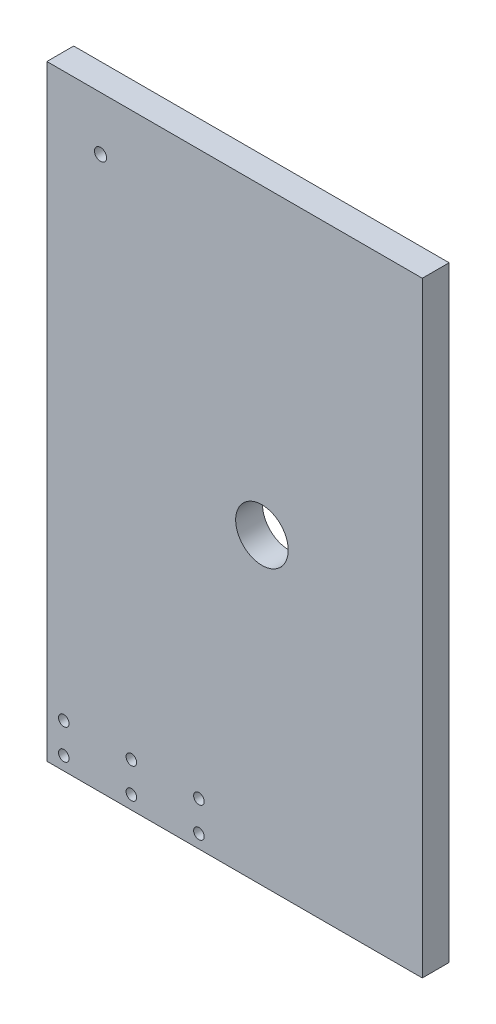
SolidWorks part; units mm, degrees
material "Balsa"
ref_plane "Front Plane" through (0, 0, 0) normal (0, 0, 1) x (1, 0, 0)
ref_plane "Top Plane" through (0, 0, 0) normal (0, 1, 0) x (1, 0, 0)
ref_plane "Right Plane" through (0, 0, 0) normal (1, 0, 0) x (0, 0, -1)
sketch "Sketch1" plane through (0, 0, 0) normal (0, 0, 1) x (1, 0, 0)
  line L0 (-63.5, 59.055) -> (-25.2727, 0.1003) construction
  line L1 (-76.2, 71.755) -> (76.2, 71.755)
  line L2 (-76.2, 71.755) -> (-76.2, -71.755)
  line L3 (-76.2, -71.755) -> (76.2, -71.755)
  line L4 (76.2, 71.755) -> (76.2, -71.755)
  line L5 (-76.2, 71.755) -> (76.2, -71.755) construction
  line L6 (-76.2, -71.755) -> (76.2, 71.755) construction
  line L7 (-25.2727, 0.1003) -> (-63.5159, 0.1003) construction
  circle A0 centre (-63.5, 59.055) radius 1.4375
  circle A1 centre (-25.2727, 0.1003) radius 6.223
  point P0 (0, 0)
  dimension "D1" = 12.446
  dimension "D2" = 70.2637
  dimension "D4" = 2.875
  dimension "D3" = 57.04
  dimension "D5" = 152.4
  dimension "D6" = 71.6547
  dimension "D7" = 12.7
  dimension "D8" = 12.7
  dimension "D9" = 143.51
extrude "Boss-Extrude1" add sketch "Sketch1" along normal blind 6.35 contours L4 L1 L2 L3 A1 A0
sketch "Sketch2" plane through (0, 0, 6.35) normal (0, 0, 1) x (1, 0, 0)
  line L1 (76.2, 71.755) -> (76.2, -71.755) construction
  line L2 (-66.0896, -64.5997) -> (90.0227, -64.5997) construction
  circle A0 centre (63.5, 11.6003) radius 76.2 construction
  circle A1 centre (63.5, 11.6003) radius 3.1115
  circle A2 centre (-25.2727, 0.1003) radius 6.223 construction
  dimension "D1" = 152.4
  dimension "D4" = 64.7
  dimension "D2" = 6.223
  dimension "D3" = 12.7
extrude "Cut-Extrude1" cut sketch "Sketch2" against normal through all contours A1
sketch "Sketch3" plane through (0, 0, 6.35) normal (0, 0, 1) x (1, 0, 0)
  circle A0 centre (-25.2727, 0.1003) radius 18.75 construction
  circle A1 centre (9.6146, -13.6519) radius 18.75 construction
  dimension "D1" = 37.5
sketch "Sketch4" plane through (0, 0, 6.35) normal (0, 0, 1) x (1, 0, 0)
  circle A0 centre (43.8491, -5.2749) radius 1.625
  circle A1 centre (43.8491, -21.2749) radius 1.625
  circle A2 centre (43.8491, -37.2749) radius 1.625
  circle A3 centre (43.8491, 10.7251) radius 1.625
  arc A4 (43.8491, 9.4751) -> (43.8491, 11.9751) centre (43.8491, 10.7251) ccw construction
  arc A5 (43.8491, -6.5249) -> (43.8491, -4.0249) centre (43.8491, -5.2749) ccw construction
  arc A6 (43.8491, -20.0249) -> (43.8491, -22.5249) centre (43.8491, -21.2749) ccw construction
  arc A7 (43.8491, -36.0249) -> (43.8491, -38.5249) centre (43.8491, -37.2749) ccw construction
  dimension "D1" = 3.25
extrude "Cut-Extrude2" cut sketch "Sketch4" against normal through all contours A0 | A1 | A2 | A3
sketch "Sketch5" plane through (0, 0, 0) normal (0, 0, -1) x (-1, 0, 0)
  line L0 (76.2, -71.755) -> (-76.2, -71.755) construction
  line L1 (-76.2, 71.755) -> (-12.7, 71.755)
  line L2 (-76.2, 71.755) -> (-76.2, -71.755)
  line L3 (-76.2, -71.755) -> (-12.7, -71.755)
  line L4 (-12.7, 71.755) -> (-12.7, -71.755)
  dimension "D1" = 63.5
extrude "Cut-Extrude3" cut sketch "Sketch5" against normal through all
sketch "Sketch6" plane through (0, 0, 0) normal (0, 0, -1) x (-1, 0, 0)
  line L0 (40.2, -65.405) -> (76.2, -65.405) construction
  line L1 (76.2, -71.755) -> (40.2, -71.755) construction
  line L2 (76.2, -71.755) -> (76.2, -61.405) construction
  line L3 (76.2, -61.405) -> (40.2, -61.405) construction
  line L4 (40.2, -71.755) -> (40.2, -61.405) construction
  line L5 (56.2, -61.405) -> (56.2, -65.405) construction
  line L6 (72.2, -61.405) -> (72.2, -65.405) construction
  line L7 (40.2, -68.58) -> (72.2, -68.58) construction
  line L8 (56.2, -65.405) -> (56.2, -71.755) construction
  line L9 (72.2, -65.405) -> (72.2, -68.58) construction
  circle A0 centre (72.2, -61.405) radius 1.25
  circle A1 centre (56.2, -61.405) radius 1.25
  circle A2 centre (40.2, -61.405) radius 1.25
  circle A3 centre (72.2, -68.58) radius 1.25
  circle A4 centre (56.2, -68.58) radius 1.25
  circle A5 centre (40.2, -68.58) radius 1.25
  point P12 (56.2, -68.58)
  point P13 (40.2, -65.405)
  dimension "D5" = 2.5
  dimension "D1" = 10.35
  dimension "D2" = 4
  dimension "D3" = 16
  dimension "D4" = 16
  dimension "D6" = 6.35
extrude "Cut-Extrude4" cut sketch "Sketch6" against normal through all
